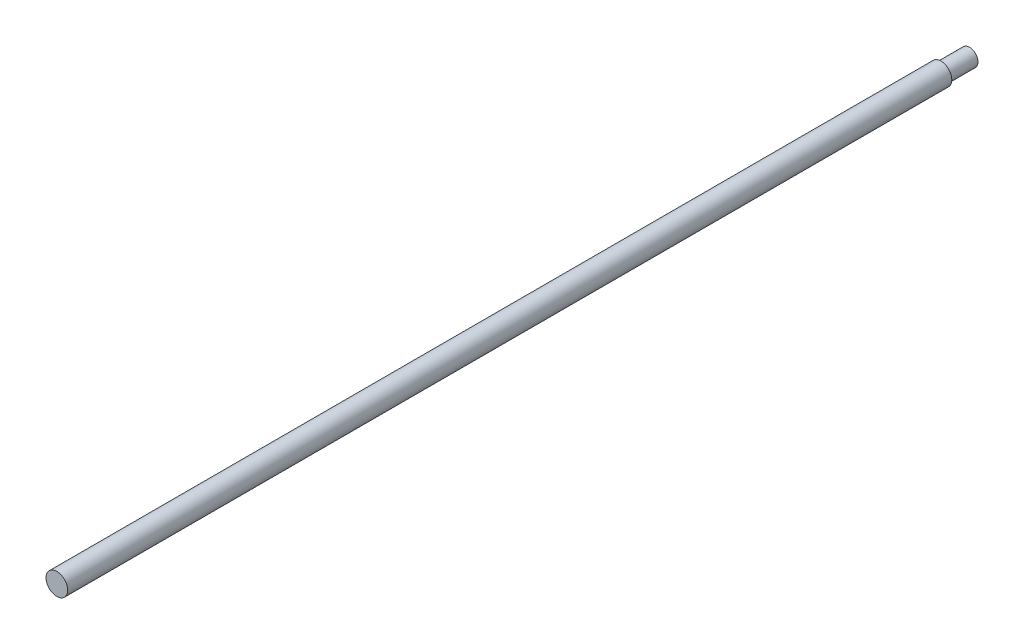
SolidWorks part; units mm, degrees
ref_plane "Front Plane" through (0, 0, 0) normal (0, 0, 1) x (1, 0, 0)
ref_plane "Top Plane" through (0, 0, 0) normal (0, 1, 0) x (1, 0, 0)
ref_plane "Right Plane" through (0, 0, 0) normal (1, 0, 0) x (0, 0, -1)
sketch "Sketch1" plane through (0, 0, 0) normal (0, 0, 1) x (1, 0, 0)
  circle A0 centre (0, 0) radius 3.8
  dimension "D1" = 7.6
extrude "Boss-Extrude1" add sketch "Sketch1" along normal blind 320
sketch "Sketch2" plane through (0, 0, 0) normal (0, 0, -1) x (-1, 0, 0)
  circle A0 centre (0, 0) radius 3
  dimension "D1" = 6
extrude "Cut-Extrude1" cut sketch "Sketch2" against normal blind 10 flip side to cut
